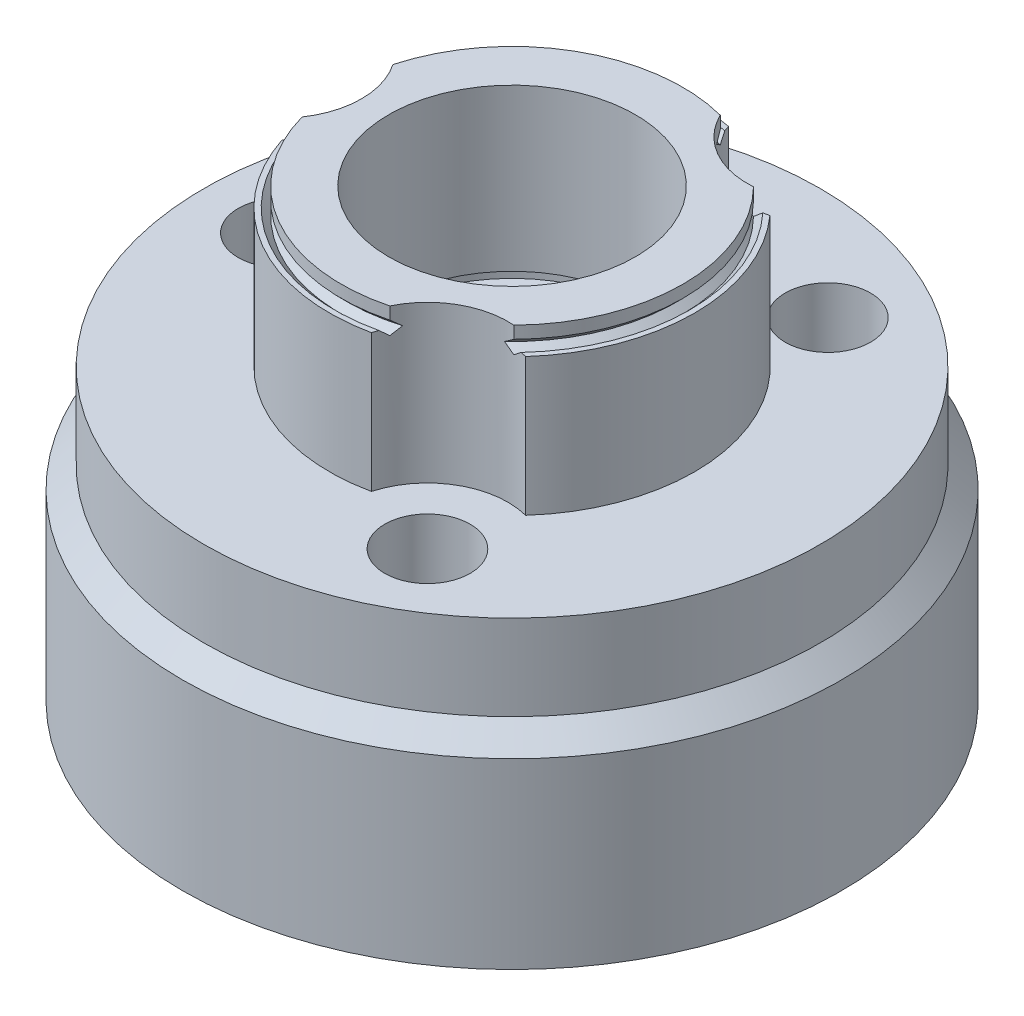
SolidWorks part; units mm, degrees
ref_plane "前视基准面" through (0, 0, 0) normal (0, 0, 1) x (1, 0, 0)
ref_plane "上视基准面" through (0, 0, 0) normal (0, 1, 0) x (1, 0, 0)
ref_plane "右视基准面" through (0, 0, 0) normal (1, 0, 0) x (0, 0, -1)
other "Configuration Table"
sketch "草图1" plane through (0, 0, 0) normal (0, 0, 1) x (1, 0, 0)
  line L0 (0, 19.2463) -> (0, -15.5803) construction
  line L1 (63, 0) -> (63, 26)
  line L2 (63, 26) -> (26, 26)
  line L3 (26, 26) -> (26, 37)
  line L4 (26, 37) -> (27, 37)
  line L5 (27, 37) -> (27, 39)
  line L6 (27, 39) -> (22, 39)
  line L7 (22, 39) -> (22, 58)
  line L8 (22, 58) -> (27, 58)
  line L9 (27, 58) -> (27, 60)
  line L10 (27, 60) -> (26, 60)
  line L11 (26, 60) -> (26, 94)
  line L12 (26, 94) -> (36, 94)
  line L13 (36, 94) -> (36, 91.4142)
  line L14 (36, 91.4142) -> (34.5858, 90)
  line L15 (34.5858, 90) -> (36, 88.5858)
  line L16 (36, 88.5858) -> (37.4142, 90)
  line L17 (37.4142, 90) -> (38.5, 90)
  line L18 (38.5, 90) -> (38.5, 61)
  line L19 (38.5, 61) -> (65, 61)
  line L20 (65, 61) -> (65, 43)
  line L21 (65, 43) -> (69.5, 38.5)
  line L22 (69.5, 38.5) -> (69.5, 0)
  line L23 (69.5, 0) -> (63, 0)
  point P23 (27, 38)
  dimension "D1" = 69.5
  dimension "D2" = 63
  dimension "D3" = 2
  dimension "D4" = 26
  dimension "D5" = 2
  dimension "D6" = 2
  dimension "D7" = 2
  dimension "D8" = 135
  dimension "D9" = 36
  dimension "D10" = 22
  dimension "D11" = 26
  dimension "D12" = 27
  dimension "D13" = 2
  dimension "D14" = 13
  dimension "D15" = 26
  dimension "D16" = 18
  dimension "D17" = 29
  dimension "D18" = 4
  dimension "D19" = 38.5
  dimension "D20" = 36
  dimension "D21" = 65
  dimension "D22" = 27
  dimension "D23" = 94
revolve "旋转1" add sketch "草图1" angle 360 about L0
sketch "草图2" plane through (0, 61, 0) normal (0, 1, 0) x (1, 0, 0)
  circle A0 centre (-48.75, 0) radius 17
  circle A1 centre (0, 0) radius 48.75 construction
  circle A2 centre (24.375, 42.2187) radius 17
  circle A3 centre (24.375, -42.2187) radius 17
  point P12 (0, 0)
  dimension "D1" = 34
  dimension "D2" = 97.5
  dimension "D3" = 3
extrude "切除-拉伸1" cut sketch "草图2" along normal up to surface (33 mm away) up to face at (0, 94, 26)
sketch "草图3" plane through (0, 61, 0) normal (0, 1, 0) x (1, 0, 0)
  circle A0 centre (24.375, 42.2187) radius 9
  circle A1 centre (24.375, -42.2187) radius 9
  circle A2 centre (-48.75, 0) radius 9
  dimension "D1" = 18
  dimension "D2" = 18
  dimension "D3" = 18
extrude "切除-拉伸2" cut sketch "草图3" against normal up to surface (35 mm away) up to face at (0, 26, 63)
